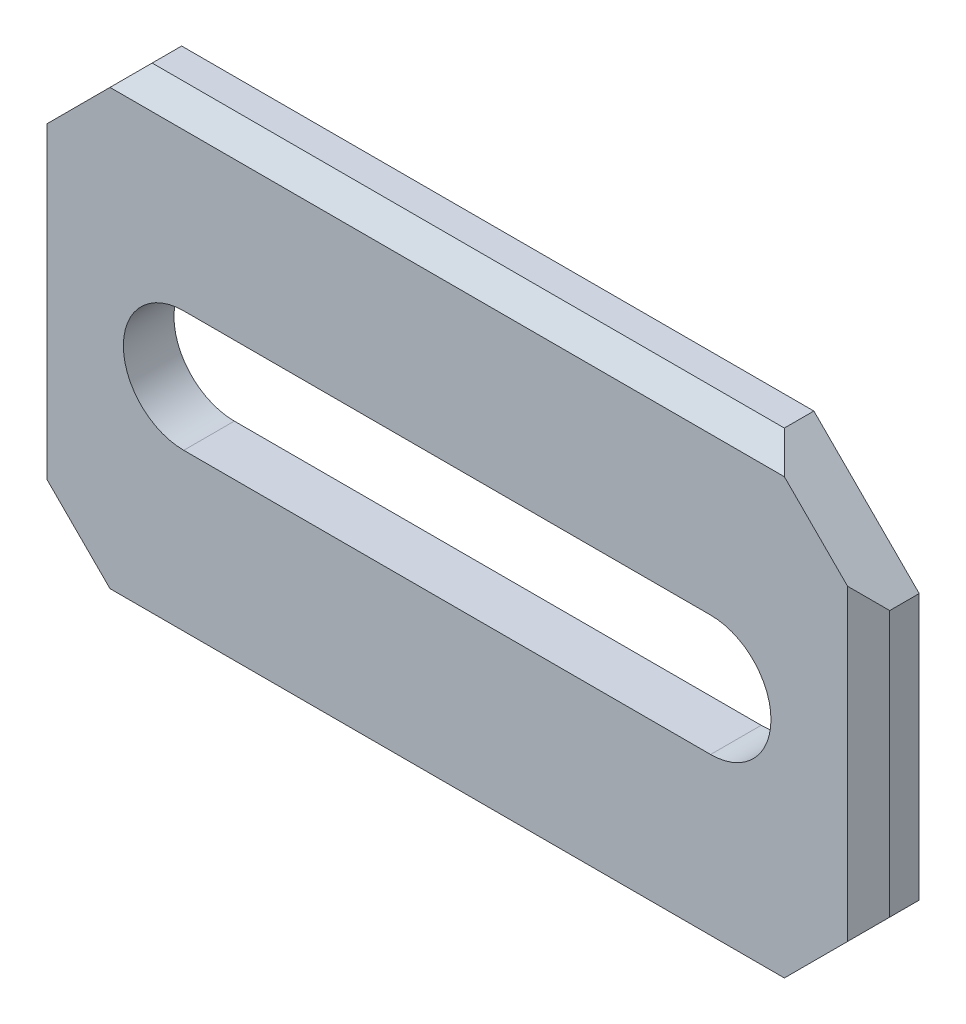
SolidWorks part; units mm, degrees
ref_plane "정면" through (0, 0, 0) normal (0, 0, 1) x (1, 0, 0)
ref_plane "윗면" through (0, 0, 0) normal (0, 1, 0) x (1, 0, 0)
ref_plane "우측면" through (0, 0, 0) normal (1, 0, 0) x (0, 0, -1)
sketch "스케치1" plane through (0, 0, 0) normal (0, 0, 1) x (1, 0, 0)
  line L0 (-12.5, 0) -> (12.5, 0) construction
  line L1 (-20, -11.3) -> (20, -11.3)
  line L2 (-20, -11.3) -> (-20, 11.3)
  line L3 (-20, 11.3) -> (20, 11.3)
  line L4 (20, -11.3) -> (20, 11.3)
  line L5 (-20, -11.3) -> (20, 11.3) construction
  line L6 (-20, 11.3) -> (20, -11.3) construction
  line L7 (-12.5, 2.8646) -> (12.5, 2.8646)
  line L8 (-12.5, -2.8646) -> (12.5, -2.8646)
  arc A0 (-12.5, 2.8646) -> (-12.5, -2.8646) centre (-12.5, 0) ccw
  arc A1 (12.5, -2.8646) -> (12.5, 2.8646) centre (12.5, 0) ccw
  point P0 (0, 0)
  point P8 (0, 0)
  dimension "D1" = 40
  dimension "D2" = 22.6
  dimension "D3" = 25
extrude "보스-돌출1" add sketch "스케치1" along normal mid plane 2.4
chamfer "모따기1" distance 5 angle 45 4 edges at (20, 11.3, 0) (20, -11.3, 0) (-20, -11.3, 0) (-20, 11.3, 0)
chamfer "모따기2" distance 1 angle 45 4 edges at (20, 0, 1.2) (-20, 0, 1.2) (0, -11.3, 1.2) (0, 11.3, 1.2)
